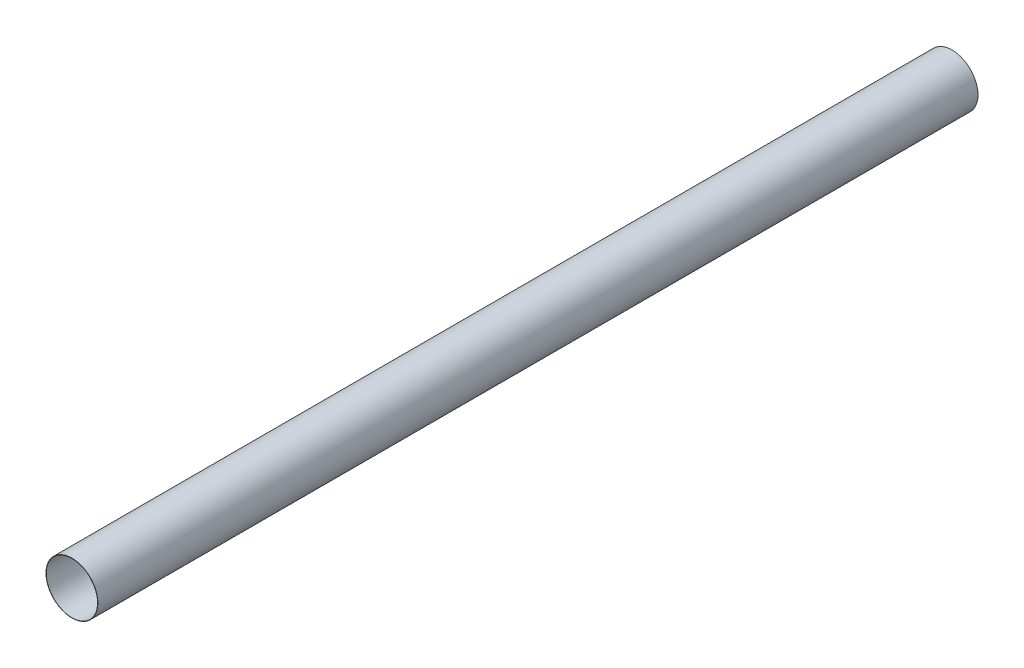
SolidWorks part; units mm, degrees
ref_plane "前视基准面" through (0, 0, 0) normal (0, 0, 1) x (1, 0, 0)
ref_plane "上视基准面" through (0, 0, 0) normal (0, 1, 0) x (1, 0, 0)
ref_plane "右视基准面" through (0, 0, 0) normal (1, 0, 0) x (0, 0, -1)
sketch "草图1" plane through (0, 0, 0) normal (0, 0, 1) x (1, 0, 0)
  circle A0 centre (0, 0) radius 8.75
  circle A1 centre (0, 0) radius 8.85
  dimension "D1" = 17.5
  dimension "D2" = 0.1
extrude "凸台-拉伸1" add sketch "草图1" along normal blind 300
sketch "草图2" plane through (0, 0, 0) normal (0, 1, 0) x (1, 0, 0)
  line L0 (0, 89.9006) -> (0, -625.8413) construction
